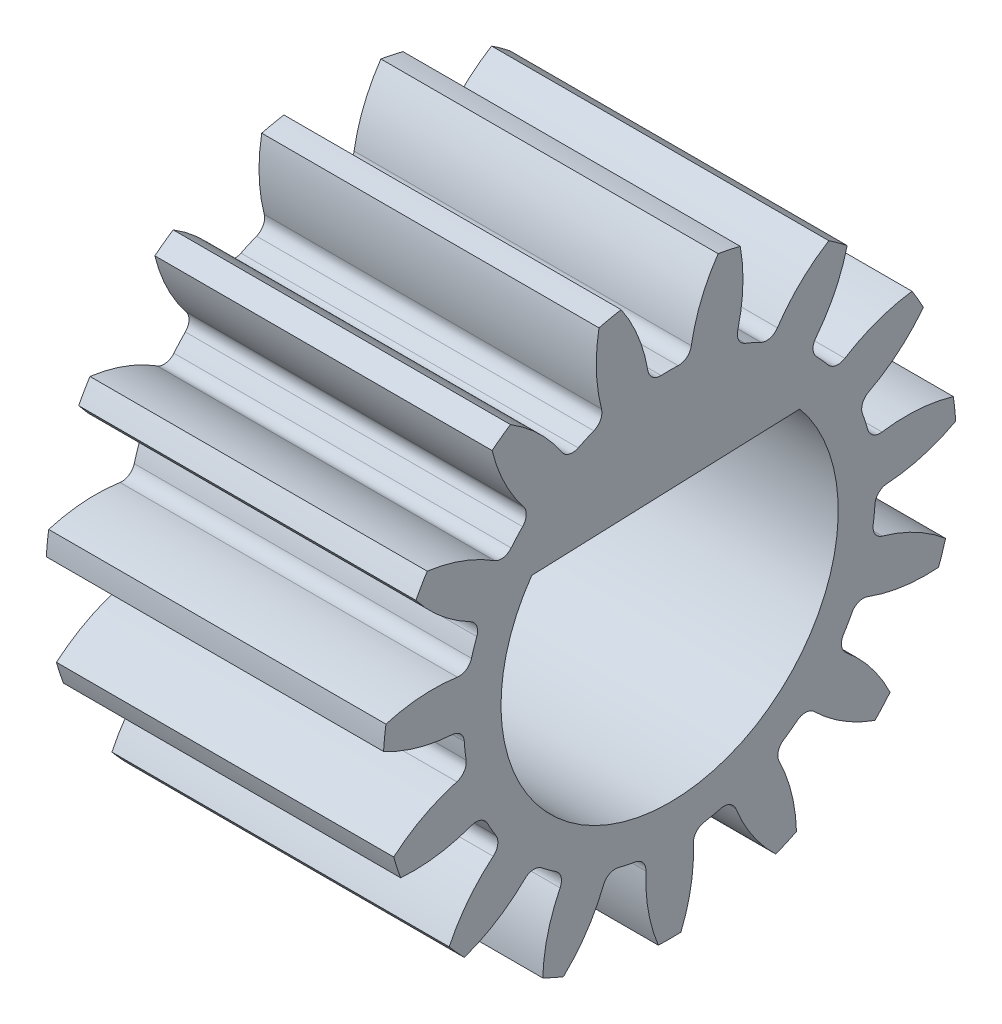
SolidWorks part; units mm, degrees
ref_plane "Front Plane" through (0, 0, 0) normal (0, 0, 1) x (1, 0, 0)
ref_plane "Top Plane" through (0, 0, 0) normal (0, 1, 0) x (1, 0, 0)
ref_plane "Right Plane" through (0, 0, 0) normal (1, 0, 0) x (0, 0, -1)
sketch "Sketch1" plane through (0, 0, 0) normal (1, 0, 0) x (0, 0, -1)
  circle A0 centre (0, 0) radius 5
  circle A1 centre (0, 0) radius 8.5
  dimension "D1" = 10
  dimension "D2" = 17
extrude "Boss-Extrude2" add sketch "Sketch1" along normal blind 10
sketch "Sketch3" plane through (10, 0, 0) normal (1, 0, 0) x (0, 0, -1)
  line L0 (0, 0) -> (0, 8.5) construction
  line L1 (-0.5979, 6.0706) -> (0, 0) construction
  line L2 (0, 4.8806) -> (-5.5984, 20.262) construction
  circle A0 centre (0, 0) radius 8.5 construction
  arc A1 (0.5979, 6.0706) -> (-0.5979, 6.0706) centre (0, 0) ccw
  arc A2 (0.9354, 7.4414) -> (-0.9354, 7.4414) centre (0, 0) ccw construction
  arc A3 (1.4375, 8.3776) -> (-1.4375, 8.3776) centre (0, 0) ccw
  arc A4 (-1.4375, 8.3776) -> (-0.5979, 6.0706) centre (-5.5182, 5.5861) cw
  arc A5 (1.4375, 8.3776) -> (0.5979, 6.0706) centre (5.5182, 5.5861) ccw
  point P17 (-0.8722, 7.277)
  dimension "D1" = 17
  dimension "D2" = 15
  dimension "D3" = 2.4
  dimension "D4" = 20
  dimension "D5" = 1.8708
extrude "Cut-Extrude1" cut sketch "Sketch3" against normal through all
fillet "Fillet1" radius 0.38 2 edges at (5, 6.0706, -0.5979) (5, 6.0706, 0.5979)
pattern_circular "CirPattern2" count 15 over 360 about axis through (0, 0, 0) along (1, 0, 0) of "Fillet1", "Cut-Extrude1"
sketch "Sketch4" plane through (10, 0, 0) normal (1, 0, 0) x (0, 0, -1)
  line L0 (-4.0879, 2.879) -> (3.8593, 3.179)
  circle A0 centre (0, 0) radius 5 construction
  arc A1 (-4.0879, 2.879) -> (3.8593, 3.179) centre (-0.0012, 0.0311) cw
  dimension "D1" = 3
extrude "Boss-Extrude3" add sketch "Sketch4" against normal up to surface (10 mm away) up to face at (0, 0, -5)
equation "\"No of teeth\"= 15"
equation "\"Module\" = 1"
equation "\"Outer Diameter\"= ( \"No of teeth\" + 2 ) * \"Module\""
equation "\"Pitch Diameter\"= \"No of teeth\" * \"Module\""
equation "\"Backlash\"= 0.3 * \"Module\""
equation "\"Arc Length\"= ( ( \"Module\" * pi ) / 2 ) + \"Backlash\""
equation "\"Fillet Radius\"= 0.38 * \"Module\""
equation "\"Bore Diameter\" = 10"
equation "\"Presseure angle\"= 20"
equation "\"Tooth Design\"= IIF ( \"Module\" <= 1.25 , 2.4 * \"Module\" , 2.25 * \"Module\" )"
equation "\"D1@Sketch1\"=\"Bore Diameter\""
equation "\"D2@Sketch1\"=\"Outer Diameter\""
equation "\"D1@Sketch3\"=\"Outer Diameter\""
equation "\"D2@Sketch3\"=\"Pitch Diameter\""
equation "\"D3@Sketch3\"=\"Tooth Design\""
equation "\"D4@Sketch3\"=\"Presseure angle\""
equation "\"D5@Sketch3\"=\"Arc Length\""
equation "\"D1@Fillet1\"=\"Fillet Radius\""
equation "\"D1@CirPattern2\"=\"No of teeth\""
